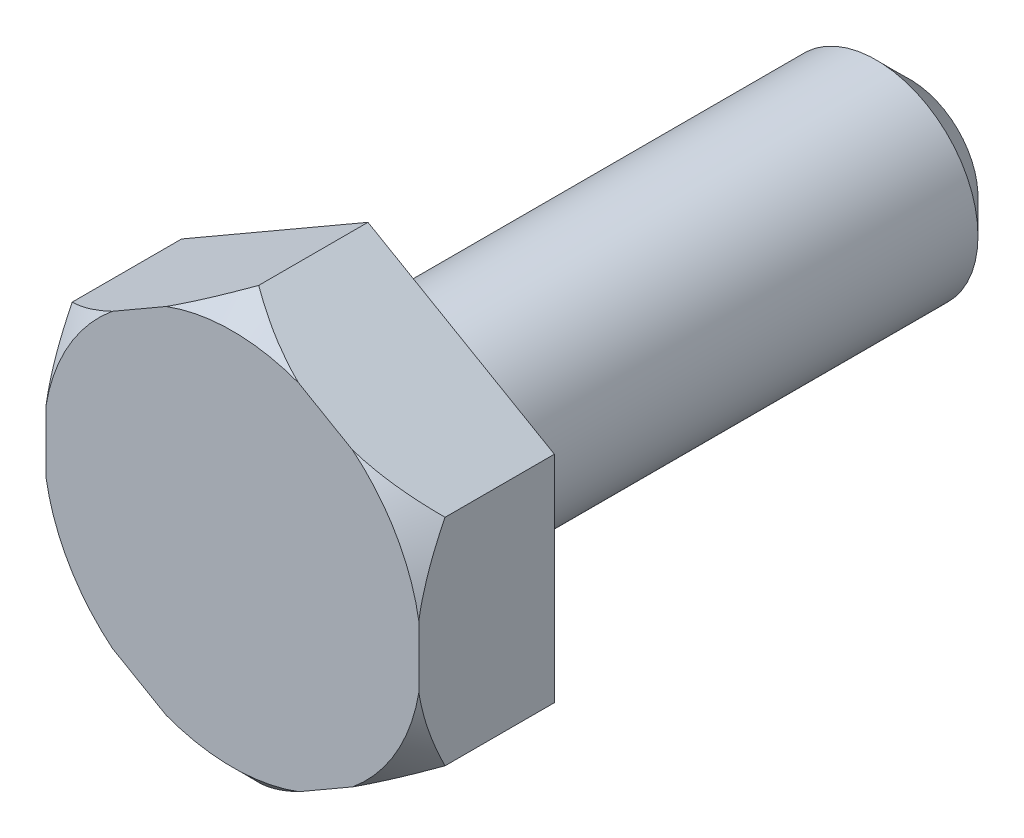
SolidWorks part; units mm, degrees
ref_plane "Спереди" through (0, 0, 0) normal (0, 0, 1) x (1, 0, 0)
ref_plane "Сверху" through (0, 0, 0) normal (0, 1, 0) x (1, 0, 0)
ref_plane "Справа" through (0, 0, 0) normal (1, 0, 0) x (0, 0, -1)
sketch "Эскиз1" plane through (0, 0, 0) normal (0, 0, 1) x (1, 0, 0)
  line L0 (0, 3.7738) -> (0, -4.1898) construction
  line L1 (-3.4469, 0) -> (3.2389, 0) construction
  line L3 (0, 3.1754) -> (-2.75, 1.5877)
  line L4 (-2.75, 1.5877) -> (-2.75, -1.5877)
  line L5 (-2.75, -1.5877) -> (0, -3.1754)
  line L6 (0, -3.1754) -> (2.75, -1.5877)
  line L7 (2.75, -1.5877) -> (2.75, 1.5877)
  line L8 (2.75, 1.5877) -> (0, 3.1754)
  circle A0 centre (0, 0) radius 2.75 construction
extrude "Вытянуть1" add sketch "Эскиз1" along normal blind 2
sketch "Эскиз2" plane through (0, 0, 0) normal (0, 0, -1) x (-1, 0, 0)
  circle A0 centre (0, 0) radius 1.5
extrude "Вытянуть2" add sketch "Эскиз2" along normal blind 8
ref_axis "Ось4" through (0, 0, 4.4653) along (0, 0, -1)
sketch "Эскиз15" plane through (0, 0, 0) normal (1, 0, 0) x (0, 0, -1)
  line L0 (-2, 3.1754) -> (-2, 2.7879)
  line L1 (-2, 1.5877) -> (-2, 3.1754) construction
  line L2 (-2, 2.7879) -> (-1.6125, 3.1754)
  line L3 (-2, 3.1754) -> (0, 3.1754) construction
  line L4 (-1.6125, 3.1754) -> (-2, 3.1754)
revolve "Вырез-Повернуть1" cut sketch "Эскиз15" angle 360 about axis through (0, 0, 4.4653) along (0, 0, -1)
ref_plane "Плоскость1" through (2.75, 0.4583, 2) normal (-0.1644, 0.9864, 0) x (-0.9864, -0.1644, 0)
chamfer "Фаска1" distance 0.5 angle 45 1 edges at (-1.5, 0, -8)
